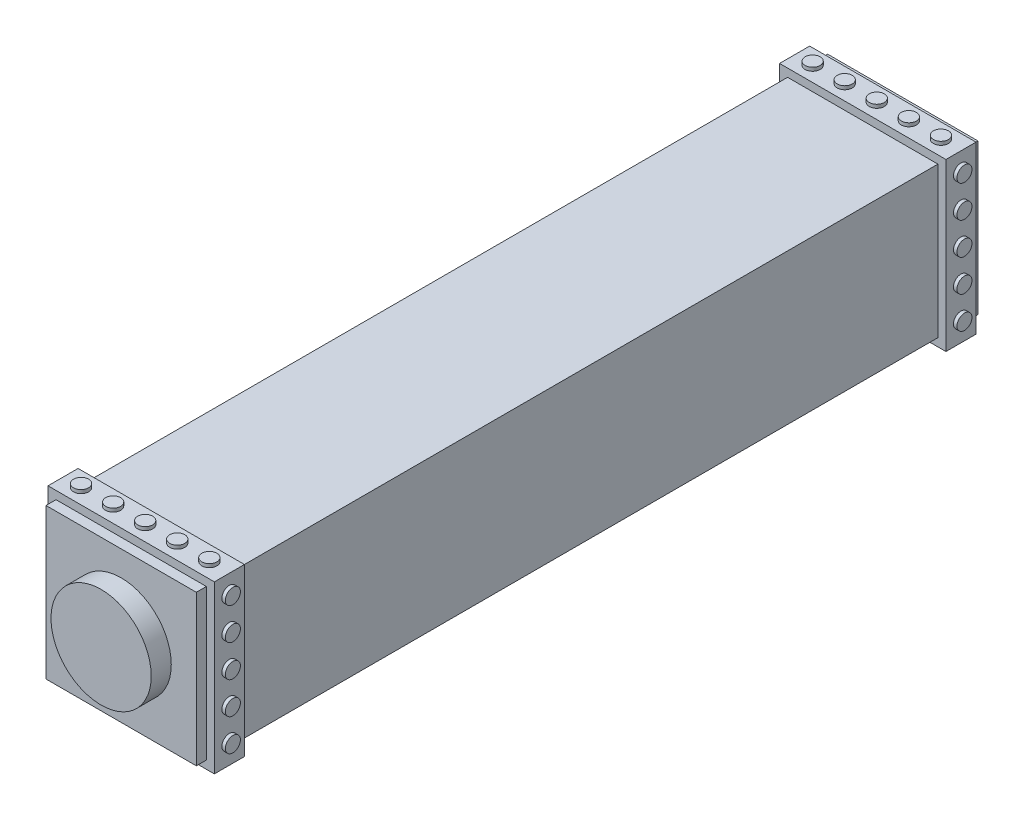
SolidWorks part; units mm, degrees
ref_plane "Front Plane" through (0, 0, 0) normal (0, 0, 1) x (1, 0, 0)
ref_plane "Top Plane" through (0, 0, 0) normal (0, 1, 0) x (1, 0, 0)
ref_plane "Right Plane" through (0, 0, 0) normal (1, 0, 0) x (0, 0, -1)
sketch "Sketch1" plane through (0, 0, 0) normal (0, 0, 1) x (1, 0, 0)
  circle A0 centre (0, 0) radius 63.5
  dimension "D1" = 127
extrude "Boss-Extrude1" add sketch "Sketch1" along normal blind 25.4
sketch "Sketch2" plane through (0, 0, 0) normal (0, 0, -1) x (-1, 0, 0)
  line L1 (-95.25, -95.25) -> (95.25, -95.25)
  line L2 (-95.25, -95.25) -> (-95.25, 95.25)
  line L3 (-95.25, 95.25) -> (95.25, 95.25)
  line L4 (95.25, -95.25) -> (95.25, 95.25)
  line L5 (-95.25, -95.25) -> (95.25, 95.25) construction
  line L6 (-95.25, 95.25) -> (95.25, -95.25) construction
  point P0 (0, 0)
  dimension "D1" = 190.5
extrude "Boss-Extrude2" add sketch "Sketch2" along normal blind 990.6
sketch "Sketch3" plane through (0, 0, -990.6) normal (0, 0, -1) x (-1, 0, 0)
  circle A0 centre (0, 0) radius 63.5
extrude "Boss-Extrude3" add sketch "Sketch3" along normal blind 25.4
sketch "Sketch4" plane through (95.25, 0, 0) normal (1, 0, 0) x (0, 0, -1)
  line L0 (12.7, 105.41) -> (12.7, -95.25)
  line L1 (12.7, -95.25) -> (50.8, -95.25)
  line L2 (990.6, -95.25) -> (0, -95.25) construction
  line L3 (12.7, 105.41) -> (50.8, 105.41)
  line L5 (50.8, 105.41) -> (50.8, -95.25)
  line L6 (0, 63.5) -> (0, -63.5) construction
  dimension "D1" = 38.1
  dimension "D2" = 12.7
  dimension "D3" = 10.16
extrude "Boss-Extrude4" add sketch "Sketch4" along normal blind 10.16
sketch "Sketch5" plane through (105.41, 0, 0) normal (1, 0, 0) x (0, 0, -1)
  line L0 (31.75, 105.41) -> (31.75, -95.25) construction
  line L1 (50.8, 105.41) -> (12.7, 105.41) construction
  line L2 (12.7, -95.25) -> (50.8, -95.25) construction
  line L3 (12.7, 95.25) -> (0, 95.25) construction
  line L4 (31.75, 82.55) -> (31.75, 41.91) construction
  circle A0 centre (31.75, 82.55) radius 9.525
  circle A1 centre (31.75, 41.91) radius 9.525
  circle A2 centre (31.75, 1.27) radius 9.525
  circle A3 centre (31.75, -39.37) radius 9.525
  circle A4 centre (31.75, -80.01) radius 9.525
  dimension "D1" = 12.7
  dimension "D2" = 19.05
  dimension "D4" = 40.64
  dimension "D3" = 5
extrude "Boss-Extrude5" add sketch "Sketch5" along normal blind 4.445
pattern_circular "CirPattern3" count 4 over 360 about axis through (0, 0, 0) along (0, 0, 1) of "Boss-Extrude5", "Boss-Extrude4"
ref_plane "Plane1" through (0, 0, -495.3) normal (0, 0, 1) x (1, 0, 0)
mirror "Mirror1" about plane through (0, 0, -495.3) normal (0, 0, 1) of "CirPattern3", "Boss-Extrude4", "Boss-Extrude5"
